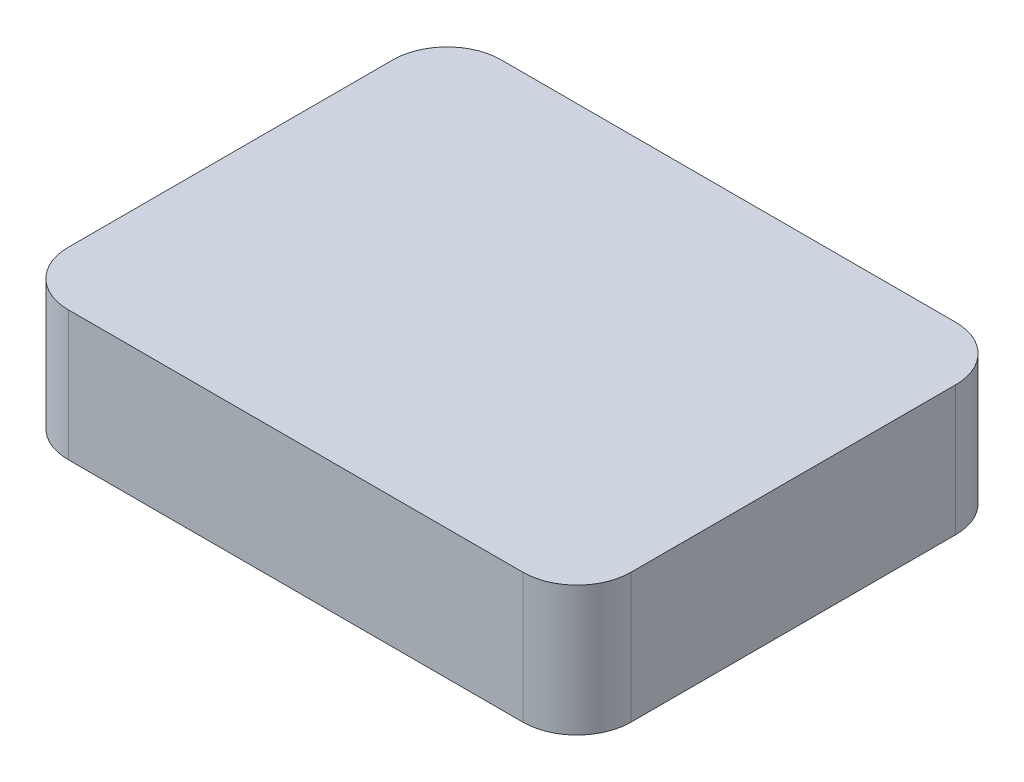
SolidWorks part; units mm, degrees
ref_plane "前视基准面" through (0, 0, 0) normal (0, 0, 1) x (1, 0, 0)
ref_plane "上视基准面" through (0, 0, 0) normal (0, 1, 0) x (1, 0, 0)
ref_plane "右视基准面" through (0, 0, 0) normal (1, 0, 0) x (0, 0, -1)
sketch "草图1" plane through (0, 0, 0) normal (0, 1, 0) x (1, 0, 0)
  line L1 (26, -20) -> (-26, -20)
  line L2 (26, -20) -> (26, 20)
  line L3 (26, 20) -> (-26, 20)
  line L4 (-26, -20) -> (-26, 20)
  line L5 (26, -20) -> (-26, 20) construction
  line L6 (26, 20) -> (-26, -20) construction
  point P0 (0, 0)
extrude "凸台-拉伸1" add sketch "草图1" along normal blind 12
fillet "圆角1" radius 5 4 edges at (-26, 6, -20) (26, 6, -20) (26, 6, 20) (-26, 6, 20)
